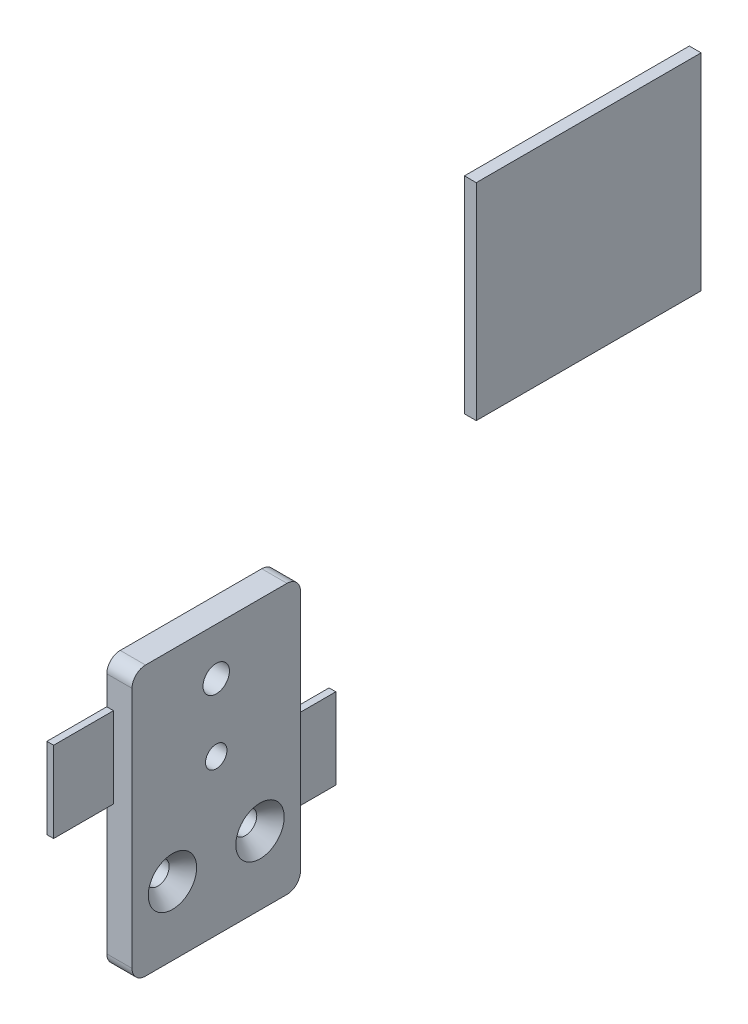
SolidWorks part; units mm, degrees
material "6061-T6 (SS)"
ref_plane "Front Plane" through (0, 0, 0) normal (0, 0, 1) x (1, 0, 0)
ref_plane "Top Plane" through (0, 0, 0) normal (0, 1, 0) x (1, 0, 0)
ref_plane "Right Plane" through (0, 0, 0) normal (1, 0, 0) x (0, 0, -1)
sketch "Sketch1" plane through (0, 0, 0) normal (1, 0, 0) x (0, 0, -1)
  line L1 (-15.875, -25.4) -> (15.875, -25.4)
  line L2 (-15.875, -25.4) -> (-15.875, 25.4)
  line L3 (-15.875, 25.4) -> (15.875, 25.4)
  line L4 (15.875, -25.4) -> (15.875, 25.4)
  line L5 (-15.875, -25.4) -> (15.875, 25.4) construction
  line L6 (-15.875, 25.4) -> (15.875, -25.4) construction
  line L9 (0, 25.4) -> (0, -25.4) construction
  point P0 (0, 0)
  dimension "D1" = 31.75
  dimension "D2" = 50.8
extrude "Boss-Extrude1" add sketch "Sketch1" along normal blind 4.7625
sketch "Sketch3" plane through (4.7625, 0, 0) normal (1, 0, 0) x (0, 0, -1)
  line L0 (-15.875, -12.4841) -> (-8.255, -12.4841) construction
  line L3 (0, 25.4) -> (0, -25.4) construction
  line L4 (15.875, 25.4) -> (-15.875, 25.4) construction
  line L5 (-15.875, -25.4) -> (15.875, -25.4) construction
  line L6 (-15.875, 25.4) -> (-15.875, -25.4) construction
  line L7 (-8.255, -12.4841) -> (8.255, -12.4841) construction
  line L8 (8.255, -12.4841) -> (15.875, -12.4841) construction
  line L9 (15.875, -25.4) -> (15.875, 25.4) construction
  point P4 (0, 16.51)
  point P15 (0, 16.51)
  point P16 (8.255, -12.4841)
  point P17 (-8.255, -12.4841)
  point P18 (0, 3.81)
  dimension "D1" = 7.62
  dimension "D2" = 28.9941
  dimension "D3" = 8.89
  dimension "D4" = 12.7
hole_wizard "CSK for #8 Flat Head Socket Cap Screw1" positions "Sketch4" profile "Sketch5" countersink size "#8" standard "ANSI Inch" end condition through all
sketch "Sketch4" plane through (4.7625, 0, 0) normal (1, 0, 0) x (0, 0, -1)
  point P0 (-8.255, -12.4841)
  point P3 (8.255, -12.4841)
sketch "Sketch5" plane through (4.7625, -12.4841, 8.255) normal (0, 1, 0) x (0, 0, -1)
  line L0 (0, 0) -> (0, 4.7625)
  line L1 (0, 4.7625) -> (2.1526, 4.7625)
  line L2 (2.1526, 4.7625) -> (2.1526, 2.7685)
  line L3 (2.1526, 2.7685) -> (4.5593, 0)
  line L5 (4.5593, 0) -> (0, 0)
  line L6 (-2.1526, 2.7685) -> (-4.5593, 0) construction
  line L11 (0, -6.35) -> (0, 107.95) construction
  dimension "Thru Hole Dia." = 4.3053
  dimension "Thru Hole Depth" = 4.7625
  dimension "Near C'Sink Dia." = 9.1186
  dimension "Near C'Sink Angle" = 82
hole_wizard "#10 Clearance Hole1" positions "Sketch6" profile "Sketch7" hole size "#10" standard "ANSI Inch" end condition through all
sketch "Sketch6" plane through (4.7625, 0, 0) normal (1, 0, 0) x (0, 0, -1)
  point P0 (0, 16.51)
sketch "Sketch7" plane through (4.7625, 16.51, 0) normal (0, 1, 0) x (0, 0, -1)
  line L0 (0, 0) -> (0, 4.7625)
  line L1 (0, 4.7625) -> (2.4892, 4.7625)
  line L2 (2.4892, 4.7625) -> (2.4892, 0)
  line L5 (2.4892, 0) -> (0, 0)
  line L11 (0, -6.35) -> (0, 107.95) construction
  dimension "Thru Hole Dia." = 4.9784
  dimension "Thru Hole Depth" = 4.7625
fillet "Fillet1" radius 2.54 4 edges at (2.3813, 25.4, -15.875) (2.3813, -25.4, -15.875) (2.3813, -25.4, 15.875) (2.3813, 25.4, 15.875)
hole_wizard "#10-32 Tapped Hole1" positions "Sketch8" profile "Sketch9" tap size "#10-32" standard "ANSI Inch" end condition through all
sketch "Sketch8" plane through (4.7625, 0, 0) normal (1, 0, 0) x (0, 0, -1)
  point P0 (0, 3.81)
sketch "Sketch9" plane through (4.7625, 3.81, 0) normal (0, 1, 0) x (0, 0, -1)
  line L0 (0, 0) -> (0, 4.7625)
  line L1 (0, 4.7625) -> (2.0193, 4.7625)
  line L2 (2.0193, 4.7625) -> (2.0193, 0)
  line L5 (2.0193, 0) -> (0, 0)
  line L11 (0, -6.35) -> (0, 107.95) construction
  dimension "Thru Tap Drill Dia." = 4.0386
  dimension "Thru Tap Drill Depth" = 4.7625
cosmetic thread "Hole Thread1" parameters "D2"=4.826
sketch "Sketch10" plane through (4.7625, 0, 0) normal (1, 0, 0) x (0, 0, -1)
  line L1 (49.0163, 72.9725) -> (91.4088, 72.9725)
  line L2 (49.0163, 72.9725) -> (49.0163, 34.1127)
  line L3 (49.0163, 34.1127) -> (91.4088, 34.1127)
  line L4 (91.4088, 72.9725) -> (91.4088, 34.1127)
extrude "Boss-Extrude2" add sketch "Sketch10" against normal offset from surface (2.2225 mm away) 2.54 separate body up to face at (0, 3.81, -2.0193)
sketch "Sketch11" plane through (0, 0, 0) normal (-1, 0, 0) x (0, 0, 1)
  line L0 (15.875, 22.86) -> (15.875, -22.86) construction
  line L1 (15.875, 17.472) -> (27.1654, 17.472)
  line L2 (15.875, 17.472) -> (15.875, 2.232)
  line L3 (15.875, 2.232) -> (27.1654, 2.232)
  line L4 (27.1654, 17.472) -> (27.1654, 2.232)
  line L5 (-15.875, -22.86) -> (-15.875, 22.86) construction
  line L6 (-15.875, -0.4005) -> (-26.0333, -0.4005)
  line L7 (-15.875, -0.4005) -> (-15.875, -15.6405)
  line L8 (-15.875, -15.6405) -> (-26.0333, -15.6405)
  line L9 (-26.0333, -0.4005) -> (-26.0333, -15.6405)
  dimension "D1" = 15.24
  dimension "D2" = 15.24
extrude "Boss-Extrude3" add sketch "Sketch11" against normal blind 1.27
